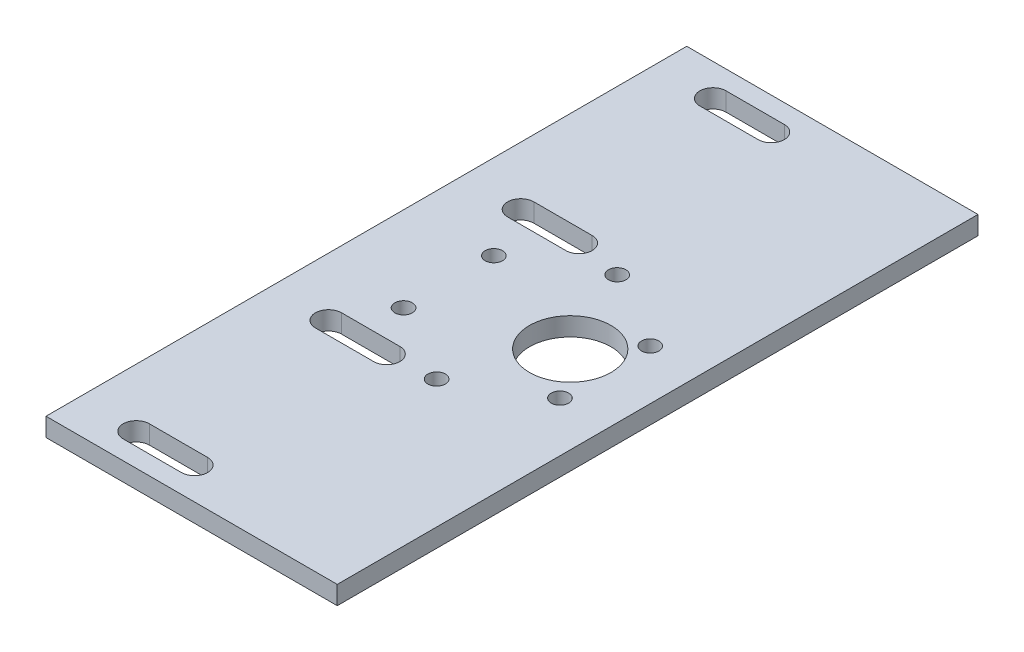
SolidWorks part; units mm, degrees
ref_plane "Front Plane" through (0, 0, 0) normal (0, 0, 1) x (1, 0, 0)
ref_plane "Top Plane" through (0, 0, 0) normal (0, 1, 0) x (1, 0, 0)
ref_plane "Right Plane" through (0, 0, 0) normal (1, 0, 0) x (0, 0, -1)
sketch "Sketch1" plane through (0, 0, 0) normal (0, 1, 0) x (1, 0, 0)
  line L1 (0, 0) -> (50, 0)
  line L2 (0, 0) -> (0, 110)
  line L3 (0, 110) -> (50, 110)
  line L4 (50, 0) -> (50, 110)
  circle A0 centre (35, 55) radius 7
  circle A1 centre (41.4236, 62.3073) radius 1.5
  circle A2 centre (41.4233, 46.8073) radius 1.5
  circle A3 centre (27.9998, 39.0575) radius 1.5
  circle A4 centre (14.5765, 46.8078) radius 1.5
  circle A5 centre (14.5768, 62.3078) radius 1.5
  circle A7 centre (28.0004, 70.0575) radius 1.5
  point P9 (28.014, 54.5575)
  point P23 (28.014, 54.5575)
  point P24 (28.0001, 54.5575)
  dimension "D1" = 15.5
  dimension "D5" = 6
  dimension "D7" = 15
  dimension "D8" = 55
  dimension "D2" = 3
  dimension "D3" = 110
  dimension "D4" = 50
  dimension "D6" = 7
  dimension "D9" = 31
extrude "Boss-Extrude1" add sketch "Sketch1" along normal blind 3.175
sketch "Sketch2" plane through (0, 3.175, 0) normal (0, 1, 0) x (1, 0, 0)
  line L6 (10, 3.25) -> (20, 3.25)
  line L7 (10, 36.25) -> (20, 36.25)
  line L8 (10, 69.25) -> (20, 69.25)
  line L9 (10, 102.25) -> (20, 102.25)
  line L10 (10, 7.75) -> (20, 7.75)
  line L11 (10, 40.75) -> (20, 40.75)
  line L12 (10, 73.75) -> (20, 73.75)
  line L13 (10, 106.75) -> (20, 106.75)
  arc A0 (10, 106.75) -> (10, 102.25) centre (10, 104.5) ccw
  arc A1 (10, 73.75) -> (10, 69.25) centre (10, 71.5) ccw
  arc A2 (10, 40.75) -> (10, 36.25) centre (10, 38.5) ccw
  arc A3 (10, 7.75) -> (10, 3.25) centre (10, 5.5) ccw
  arc A4 (20, 102.25) -> (20, 106.75) centre (20, 104.5) ccw
  arc A5 (20, 69.25) -> (20, 73.75) centre (20, 71.5) ccw
  arc A6 (20, 3.25) -> (20, 7.75) centre (20, 5.5) ccw
  arc A7 (20, 36.25) -> (20, 40.75) centre (20, 38.5) ccw
  dimension "D1" = 4.5
extrude "Cut-Extrude1" cut sketch "Sketch2" against normal blind 10
